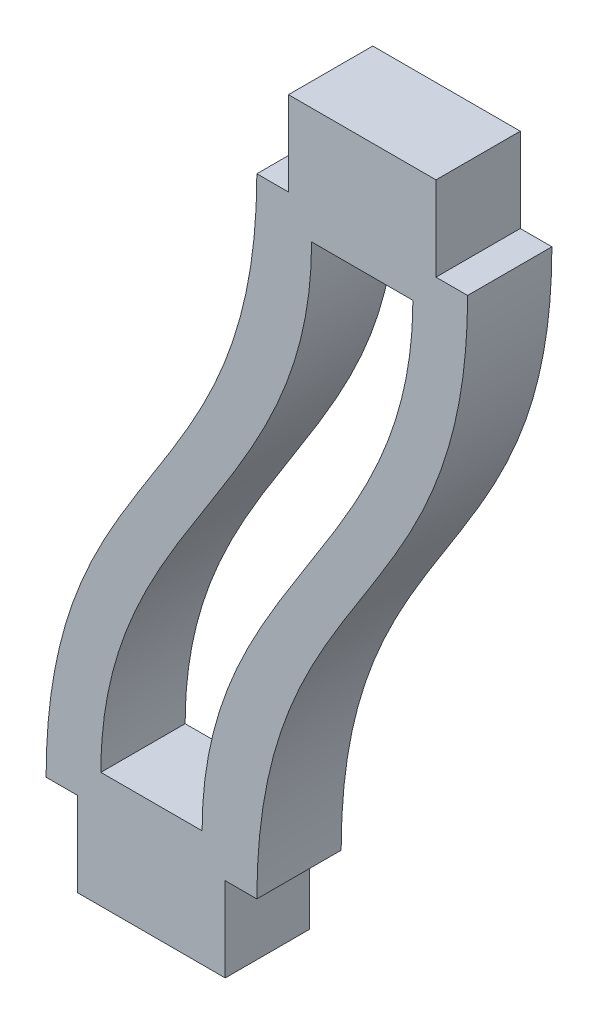
SolidWorks part; units mm, degrees
ref_plane "Plan de face" through (0, 0, 0) normal (0, 0, 1) x (1, 0, 0)
ref_plane "Plan de dessus" through (0, 0, 0) normal (0, 1, 0) x (1, 0, 0)
ref_plane "Plan de droite" through (0, 0, 0) normal (1, 0, 0) x (0, 0, -1)
sketch "Esquisse1" plane through (0, 0, 0) normal (0, 0, 1) x (1, 0, 0)
  line L0 (0, 0) -> (7, 0)
  line L1 (7, 0) -> (7, 4)
  line L2 (7, 4) -> (8.5, 4)
  line L3 (0, 0) -> (0, 4)
  line L4 (0, 4) -> (-1.5, 4)
  line L7 (-1.5, 4) -> (-1.5, 18.0184) construction
  line L8 (-1.5, 18.0184) -> (8.5, 19.7816) construction
  line L9 (8.5, 19.7816) -> (8.5, 33.8) construction
  line L10 (8.5, 4) -> (8.5, 18.0184) construction
  line L11 (8.5, 18.0184) -> (18.5, 19.7816) construction
  line L12 (-7.6494, 0) -> (-7.6494, 37.8) construction
  line L13 (18.5, 19.7816) -> (18.5, 33.8) construction
  line L14 (8.5, 33.8) -> (10, 33.8)
  line L15 (10, 33.8) -> (10, 37.8)
  line L16 (10, 37.8) -> (17, 37.8)
  line L23 (17, 37.8) -> (17, 33.8)
  line L24 (17, 33.8) -> (18.5, 33.8)
  spline S0 degree 3 poles (-1.5, 4) (-1.5, 18.0184) (8.5, 19.7816) (8.5, 33.8) knots 0 0 0 0 1 1 1 1
  spline S1 degree 3 poles (8.5, 4) (8.5, 18.0184) (18.5, 19.7816) (18.5, 33.8) knots 0 0 0 0 1 1 1 1
  dimension "D1" = 100
  dimension "D2" = 7
  dimension "D3" = 4
  dimension "D4" = 37.8
  dimension "D5" = 10
  dimension "D6" = 10
extrude "Boss.-Extru.1" add sketch "Esquisse1" along normal blind 4
sketch "Esquisse2" plane through (0, 0, 4) normal (0, 0, 1) x (1, 0, 0)
  line L0 (1.0981, 5.5) -> (1.0981, 16.5685) construction
  line L1 (1.0981, 16.5685) -> (11.0981, 21.2315) construction
  line L2 (11.0981, 21.2315) -> (11.0981, 32.3) construction
  line L3 (5.9019, 5.5) -> (5.9019, 16.5685) construction
  line L4 (5.9019, 16.5685) -> (15.9019, 21.2315) construction
  line L5 (15.9019, 21.2315) -> (15.9019, 32.3) construction
  line L6 (11.0981, 32.3) -> (15.9019, 32.3)
  line L7 (1.0981, 5.5) -> (5.9019, 5.5)
  line L8 (-1.5, 4) -> (1.0981, 5.5) construction
  line L9 (8.5, 4) -> (5.9019, 5.5) construction
  line L10 (18.5, 33.8) -> (15.9019, 32.3) construction
  line L11 (8.5, 33.8) -> (11.0981, 32.3) construction
  line L13 (0, 0) -> (7, 0) construction
  spline S0 degree 3 poles (1.0981, 5.5) (1.0981, 16.5685) (11.0981, 21.2315) (11.0981, 32.3) knots 0 0 0 0 1 1 1 1
  spline S3 degree 3 poles (5.9019, 5.5) (5.9019, 16.5685) (15.9019, 21.2315) (15.9019, 32.3) knots 0 0 0 0 1 1 1 1
  dimension "D1" = 115
  dimension "D2" = 3
  dimension "D3" = 30
extrude "Enlèv. mat.-Extru.1" cut sketch "Esquisse2" against normal up to next
